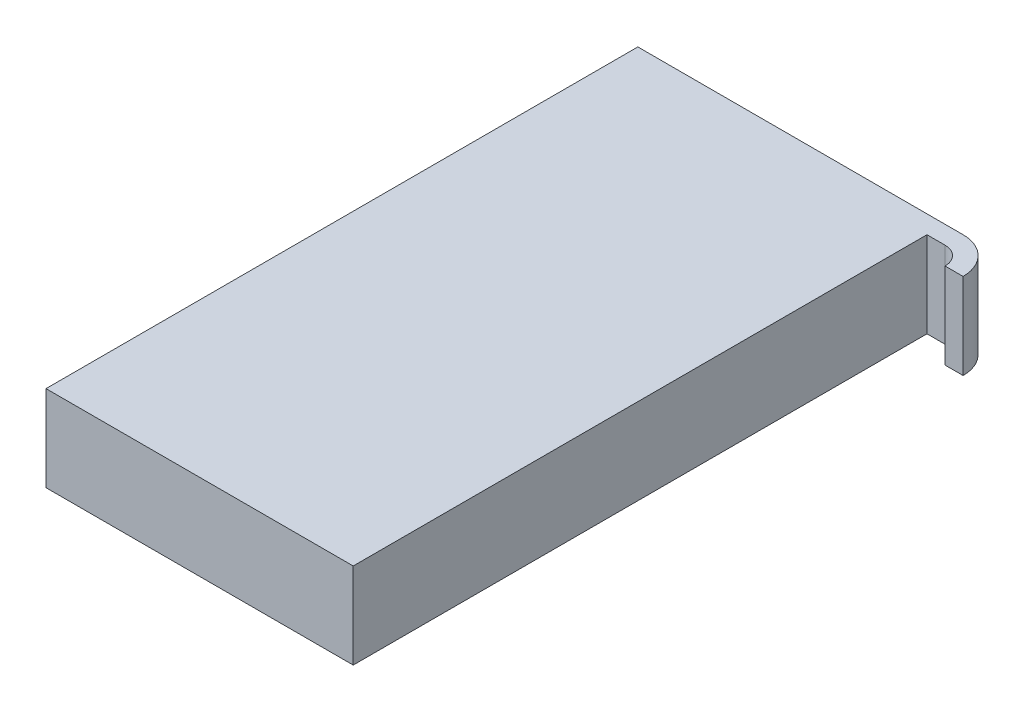
SolidWorks part; units mm, degrees
ref_plane "Front Plane" through (0, 0, 0) normal (0, 0, 1) x (1, 0, 0)
ref_plane "Top Plane" through (0, 0, 0) normal (0, 1, 0) x (1, 0, 0)
ref_plane "Right Plane" through (0, 0, 0) normal (1, 0, 0) x (0, 0, -1)
sketch "Sketch1" plane through (0, 0, 0) normal (0, 1, 0) x (1, 0, 0)
  line L0 (17, 32.75) -> (19, 32.75)
  line L1 (-17, -32.75) -> (17, -32.75)
  line L2 (-17, -32.75) -> (-17, 32.75)
  line L3 (-17, 32.75) -> (17, 32.75)
  line L4 (17, -32.75) -> (17, 32.75)
  line L5 (-17, -32.75) -> (17, 32.75) construction
  line L6 (-17, 32.75) -> (17, -32.75) construction
  line L7 (23, 28.75) -> (21, 28.75)
  line L8 (19, 30.75) -> (17, 30.75)
  arc A0 (19, 32.75) -> (23, 28.75) centre (19, 28.75) cw
  arc A1 (21, 28.75) -> (19, 30.75) centre (19, 28.75) ccw
  point P0 (0, 0)
  point P5 (20.5977, 29.994)
  point P12 (0, 0)
  dimension "D1" = 65.5
  dimension "D6" = 2
  dimension "D2" = 34
  dimension "D3" = 2
  dimension "D4" = 2
  dimension "D5" = 2
extrude "Boss-Extrude1" add sketch "Sketch1" along normal blind 9.5 contours L1 L4 L3 L2 | A1 L7 A0 L0 L4 L8
